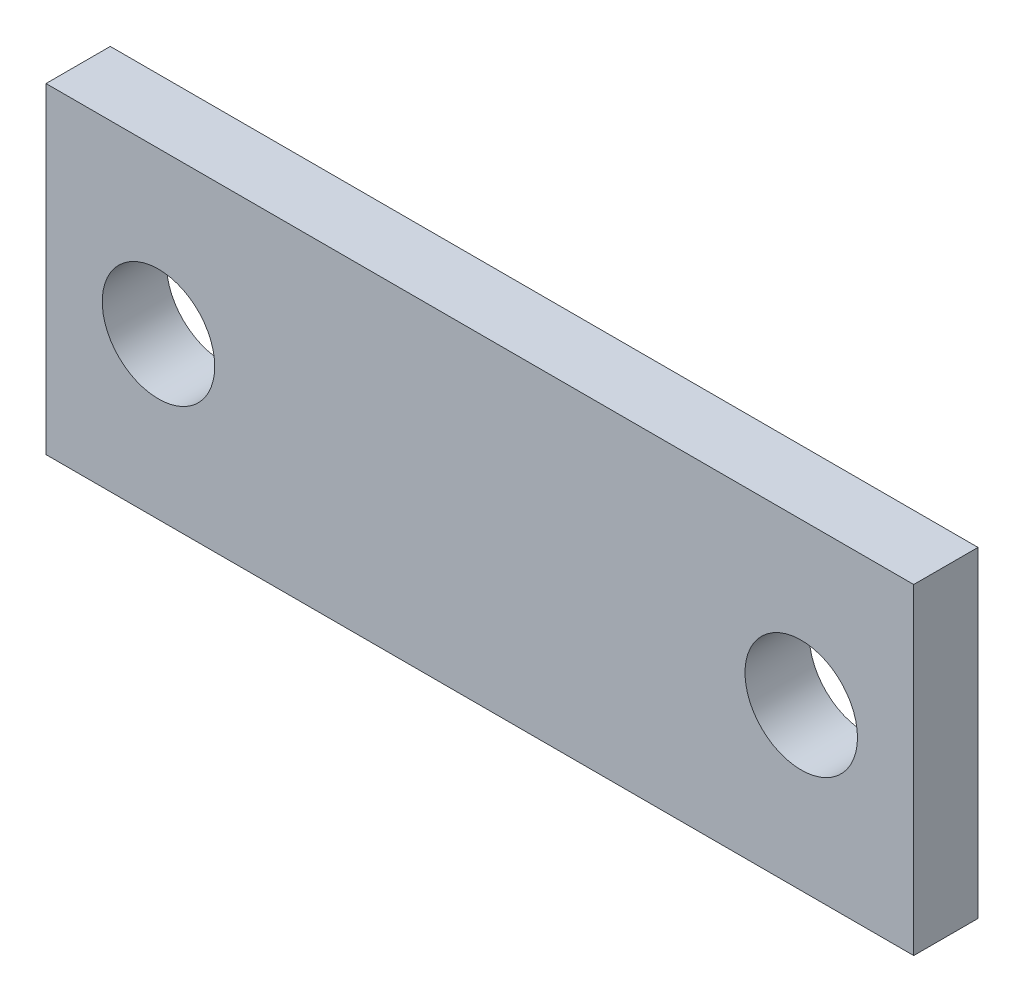
SolidWorks part; units mm, degrees
ref_plane "Plan de face" through (0, 0, 0) normal (0, 0, 1) x (1, 0, 0)
ref_plane "Plan de dessus" through (0, 0, 0) normal (0, 1, 0) x (1, 0, 0)
ref_plane "Plan de droite" through (0, 0, 0) normal (1, 0, 0) x (0, 0, -1)
sketch "Esquisse1" plane through (0, 0, 0) normal (0, 0, 1) x (1, 0, 0)
  line L1 (-13.5, 5) -> (13.5, 5)
  line L2 (-13.5, 5) -> (-13.5, -5)
  line L3 (-13.5, -5) -> (13.5, -5)
  line L4 (13.5, 5) -> (13.5, -5)
  circle A0 centre (-10, 0) radius 1.75
  circle A1 centre (10, 0) radius 1.75
  dimension "D5" = 10
  dimension "D1" = 13.5
  dimension "D2" = 27
  dimension "D3" = 5
  dimension "D4" = 10
  dimension "D6" = 10
extrude "Boss.-Extru.1" add sketch "Esquisse1" along normal blind 2
